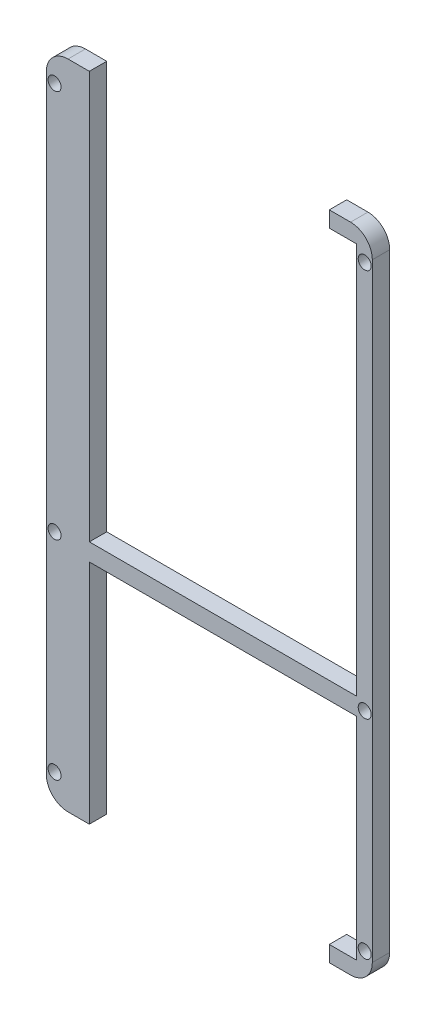
SolidWorks part; units mm, degrees
ref_plane "Front Plane" through (0, 0, 0) normal (0, 0, 1) x (1, 0, 0)
ref_plane "Top Plane" through (0, 0, 0) normal (0, 1, 0) x (1, 0, 0)
ref_plane "Right Plane" through (0, 0, 0) normal (1, 0, 0) x (0, 0, -1)
sketch "Sketch1" plane through (0, 0, 0) normal (0, 0, 1) x (1, 0, 0)
  line L0 (-65.612, -420.1) -> (-65.612, -435) construction
  line L1 (-65.612, -415.2) -> (-65.612, -425) construction
  line L2 (-65.612, -435) -> (-55.612, -435) construction
  line L3 (69.488, -135) -> (84.388, -135) construction
  line L4 (74.388, -135) -> (64.588, -135) construction
  line L5 (84.388, -135) -> (84.388, -145) construction
  line L6 (-65.612, -435) -> (-65.612, -135)
  line L11 (-65.612, -135) -> (-45.812, -135)
  line L21 (84.388, -135) -> (84.388, -435)
  line L23 (77.088, -154.8) -> (77.088, -142.3)
  line L24 (77.088, -142.3) -> (64.588, -142.3)
  line L25 (64.588, -142.3) -> (64.588, -135)
  line L26 (64.588, -135) -> (84.388, -135)
  line L30 (-45.812, -135) -> (-45.812, -322.5)
  line L31 (-45.812, -322.5) -> (77.088, -322.5)
  line L32 (77.088, -296.5) -> (77.088, -356.5) construction
  line L33 (77.088, -322.5) -> (77.088, -154.8)
  line L34 (-65.612, -435) -> (-45.812, -435)
  line L35 (-45.812, -435) -> (-45.812, -330.5)
  line L36 (-45.812, -330.5) -> (77.088, -330.5)
  line L37 (77.088, -330.5) -> (77.088, -427.7)
  line L38 (77.088, -427.7) -> (64.588, -427.7)
  line L39 (64.588, -427.7) -> (64.588, -435)
  line L41 (64.588, -435) -> (84.388, -435)
  circle A0 centre (-61.812, -326.5) radius 2 construction
  dimension "D1" = 4
  dimension "D2" = 4
extrude "Lid" add sketch "Sketch1" along normal blind 8
sketch "Sketch2" plane through (0, 0, 8) normal (0, 0, 1) x (1, 0, 0)
  circle A0 centre (80.888, -147.8) radius 3
  circle A1 centre (-61.812, -147.8) radius 3
  circle A2 centre (-61.812, -326.5) radius 3
  circle A3 centre (80.888, -326.5) radius 3
  circle A4 centre (80.888, -422.2) radius 3
  circle A5 centre (-61.812, -422.2) radius 3
  circle A6 centre (80.888, -147.8) radius 2 construction
  circle A7 centre (80.888, -326.5) radius 2 construction
  circle A8 centre (80.888, -422.2) radius 2 construction
  circle A9 centre (-61.812, -422.2) radius 2 construction
  circle A10 centre (-61.812, -326.5) radius 2 construction
  circle A11 centre (-61.812, -147.8) radius 2 construction
  dimension "D1" = 6
extrude "InsetScrewHoles" cut sketch "Sketch2" against normal blind 5
sketch "Sketch3" plane through (0, 0, 3) normal (0, 0, 1) x (1, 0, 0)
  circle A0 centre (-61.812, -147.8) radius 1.75
  circle A1 centre (80.888, -147.8) radius 1.75
  circle A2 centre (80.888, -326.5) radius 1.75
  circle A3 centre (-61.812, -326.5) radius 1.75
  circle A4 centre (80.888, -422.2) radius 1.75
  circle A5 centre (-61.812, -422.2) radius 1.75
  dimension "D1" = 3.5
extrude "ScrewHoles" cut sketch "Sketch3" against normal through all
fillet "Fillet2" radius 10 4 edges at (-65.612, -135, 4) (84.388, -135, 4) (84.388, -435, 4) (-65.612, -435, 4)
chamfer "Chamfer1" distance 2 angle 45 1 edges at (77.088, -232.4, 0)
